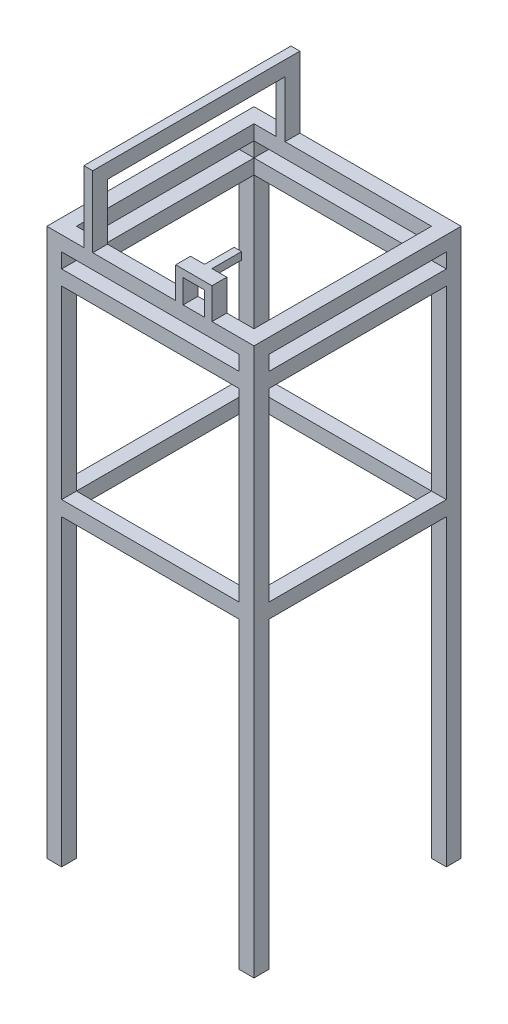
SolidWorks part; units mm, degrees
ref_plane "Alzado" through (0, 0, 0) normal (0, 0, 1) x (1, 0, 0)
ref_plane "Planta" through (0, 0, 0) normal (0, 1, 0) x (1, 0, 0)
ref_plane "Vista lateral" through (0, 0, 0) normal (1, 0, 0) x (0, 0, -1)
sketch "Croquis1" plane through (0, 0, 0) normal (0, 1, 0) x (1, 0, 0)
  line L1 (0, 0) -> (600, 0)
  line L2 (0, 0) -> (0, 600)
  line L3 (0, 600) -> (600, 600)
  line L4 (600, 0) -> (600, 600)
  line L5 (-50, -50) -> (650, -50)
  line L6 (-50, -50) -> (-50, 650)
  line L7 (-50, 650) -> (650, 650)
  line L8 (650, -50) -> (650, 650)
  dimension "D1" = 50
  dimension "D2" = 600
  dimension "D3" = 700
  dimension "D4" = 50
  dimension "D5" = 50
  dimension "D6" = 600
extrude "Saliente-Extruir1" add sketch "Croquis1" along normal blind 50
sketch "Croquis2" plane through (0, 0, 0) normal (0, -1, 0) x (1, 0, 0)
  line L0 (-50, -650) -> (-50, 50) construction
  line L1 (600, 0) -> (650, 0)
  line L2 (600, 0) -> (600, 50)
  line L3 (600, 50) -> (650, 50)
  line L4 (650, 0) -> (650, 50)
  line L5 (0, 0) -> (-50, 0)
  line L6 (0, 0) -> (0, 50)
  line L7 (0, 50) -> (-50, 50)
  line L8 (-50, 0) -> (-50, 50)
  line L9 (650, -650) -> (-50, -650) construction
  line L10 (0, -600) -> (-50, -600)
  line L11 (0, -600) -> (0, -650)
  line L12 (0, -650) -> (-50, -650)
  line L13 (-50, -600) -> (-50, -650)
  line L14 (600, -600) -> (650, -600)
  line L15 (600, -600) -> (600, -650)
  line L16 (600, -650) -> (650, -650)
  line L17 (650, -600) -> (650, -650)
extrude "Saliente-Extruir2" add sketch "Croquis2" along normal blind 1800
ref_plane "Plano1" through (0, -725, 0) normal (0, -1, 0) x (-1, 0, 0)
sketch "Croquis3" plane through (0, -725, 0) normal (0, -1, 0) x (-1, 0, 0)
  line L1 (50, -50) -> (-650, -50)
  line L2 (50, -50) -> (50, 650)
  line L3 (50, 650) -> (-650, 650)
  line L4 (-650, -50) -> (-650, 650)
  line L5 (0, 0) -> (-600, 0)
  line L6 (0, 0) -> (0, 600)
  line L7 (0, 600) -> (-600, 600)
  line L8 (-600, 0) -> (-600, 600)
extrude "Saliente-Extruir3" add sketch "Croquis3" along normal blind 50
ref_plane "Plano2" through (0, -50, 0) normal (0, -1, 0) x (-1, 0, 0)
sketch "Croquis4" plane through (0, -50, 0) normal (0, -1, 0) x (-1, 0, 0)
  line L1 (50, -50) -> (-650, -50)
  line L2 (50, -50) -> (50, 650)
  line L3 (50, 650) -> (-650, 650)
  line L4 (-650, -50) -> (-650, 650)
  line L5 (-600, 600) -> (0, 600)
  line L6 (-600, 600) -> (-600, 0)
  line L7 (-600, 0) -> (0, 0)
  line L8 (0, 600) -> (0, 0)
extrude "Saliente-Extruir4" add sketch "Croquis4" along normal blind 50
sketch "Croquis6" plane through (0, 0, 50) normal (0, 0, 1) x (1, 0, 0)
  line L0 (0, 50) -> (600, 50) construction
  line L1 (-50, 50) -> (650, 50) construction
  line L2 (0, 0) -> (600, 0) construction
  line L3 (508.0069, 0) -> (385.4762, 0)
  line L4 (508.0069, 0) -> (508.0069, 155)
  line L5 (508.0069, 155) -> (385.4762, 155)
  line L6 (385.4762, 0) -> (385.4762, 155)
  line L8 (483.0069, 50) -> (410.4762, 50)
  line L9 (483.0069, 50) -> (483.0069, 130)
  line L10 (483.0069, 130) -> (410.4762, 130)
  line L11 (410.4762, 50) -> (410.4762, 130)
  point P14 (446.7416, 130)
  point P17 (410.4762, 90)
  dimension "D1" = 25
  dimension "D2" = 25
  dimension "D3" = 25
  dimension "D4" = 80
extrude "Saliente-Extruir5" add sketch "Croquis6" against normal blind 50
sketch "Croquis7" plane through (0, 0, 0) normal (0, 0, -1) x (-1, 0, 0)
  line L0 (-410.4762, 130) -> (-483.0069, 130) construction
  line L1 (-483.0069, 130) -> (-483.0069, 155) construction
  line L2 (-508.0069, 155) -> (-385.4762, 155) construction
  line L3 (-483.0069, 155) -> (-410.4762, 155) construction
  line L4 (-410.4762, 155) -> (-410.4762, 130) construction
  line L6 (-432.9762, 130) -> (-457.9762, 130)
  line L7 (-432.9762, 130) -> (-432.9762, 155)
  line L8 (-432.9762, 155) -> (-457.9762, 155)
  line L9 (-457.9762, 130) -> (-457.9762, 155)
  dimension "D1" = 25
  dimension "D2" = 22.5
extrude "Saliente-Extruir6" add sketch "Croquis7" along normal blind 100
ref_plane "Plano3" through (90, 0, 0) normal (-1, 0, 0) x (0, 0, 1)
sketch "Croquis9" plane through (90, 0, 0) normal (-1, 0, 0) x (0, 0, 1)
  line L0 (0, 50) -> (50, 50)
  line L1 (-650, 50) -> (-600, 50)
  line L2 (-650, 50) -> (-650, 290)
  line L3 (-650, 290) -> (50, 290)
  line L4 (50, 50) -> (50, 290)
  line L11 (-600, 50) -> (-600, 240)
  line L12 (-600, 240) -> (0, 240)
  line L13 (0, 50) -> (0, 240)
  dimension "D1" = 240
  dimension "D2" = 50
extrude "Saliente-Extruir7" add sketch "Croquis9" along normal mid plane 30 from offset 0
